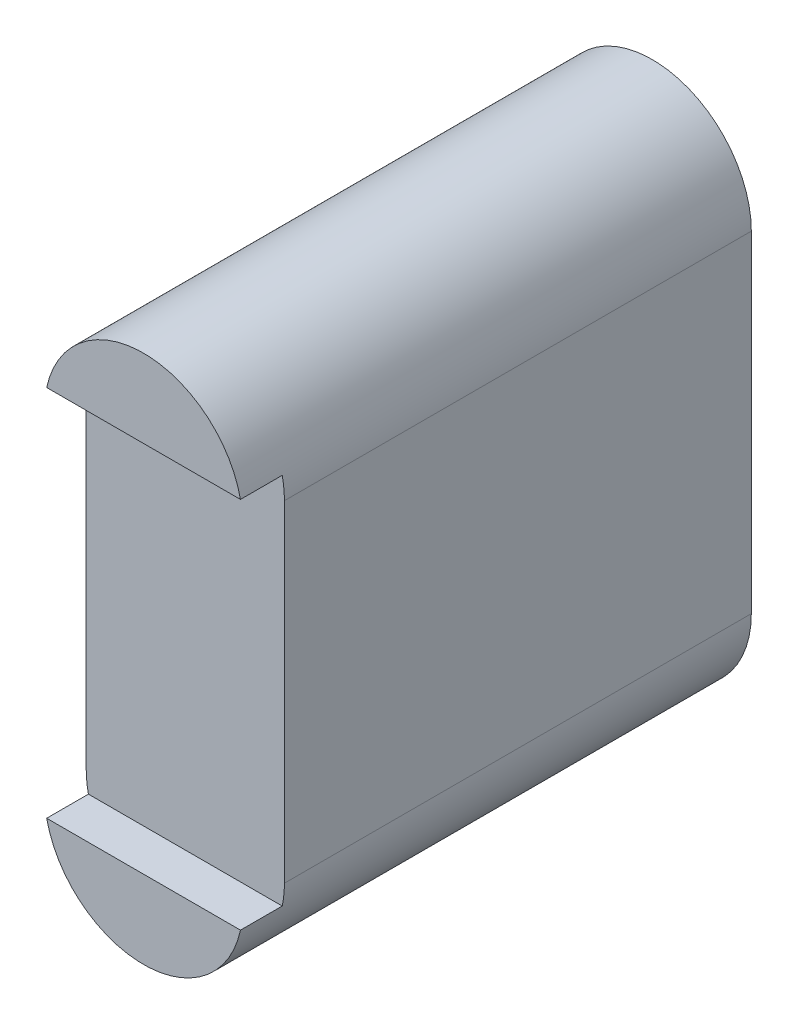
SolidWorks part; units mm, degrees
ref_plane "Спереди" through (0, 0, 0) normal (0, 0, 1) x (1, 0, 0)
ref_plane "Сверху" through (0, 0, 0) normal (0, 1, 0) x (1, 0, 0)
ref_plane "Справа" through (0, 0, 0) normal (1, 0, 0) x (0, 0, -1)
sketch "Эскиз1" plane through (0, 0, 0) normal (0, 0, 1) x (1, 0, 0)
  line L2 (-38, -63.5) -> (-38, 63.5)
  line L4 (38, -63.5) -> (38, 63.5)
  line L5 (-38, -63.5) -> (38, 63.5) construction
  line L6 (-38, 63.5) -> (38, -63.5) construction
  arc A0 (-38, 63.5) -> (38, 63.5) centre (0, 63.5) cw
  arc A1 (-38, -63.5) -> (38, -63.5) centre (0, -63.5) ccw
  point P0 (0, 0)
  point P8 (0, 101.5)
  point P9 (0, -101.5)
  dimension "D3" = 203
  dimension "D2" = 76
extrude "Бобышка-Вытянуть1" add sketch "Эскиз1" along normal blind 195 contours A0 L4 A1 L2
sketch "Эскиз2" plane through (0, 0, 195) normal (0, 0, 1) x (1, 0, 0)
  line L0 (-38, -63.5) -> (-38, 63.5) construction
  line L1 (-38, 71.5) -> (38, 71.5)
  line L2 (-38, 71.5) -> (-38, -71.5)
  line L3 (-38, -71.5) -> (38, -71.5)
  line L4 (38, 71.5) -> (38, -71.5)
  line L5 (38, -63.5) -> (38, 63.5) construction
  arc A0 (-38, -63.5) -> (38, -63.5) centre (0, -63.5) ccw construction
  arc A1 (38, 63.5) -> (-38, 63.5) centre (0, 63.5) ccw construction
  point P8 (0, -101.5)
  point P12 (0, 101.5)
  dimension "D1" = 143
  dimension "D2" = 30
  dimension "D3" = 30
extrude "Вырез-Вытянуть1" cut sketch "Эскиз2" against normal blind 16
